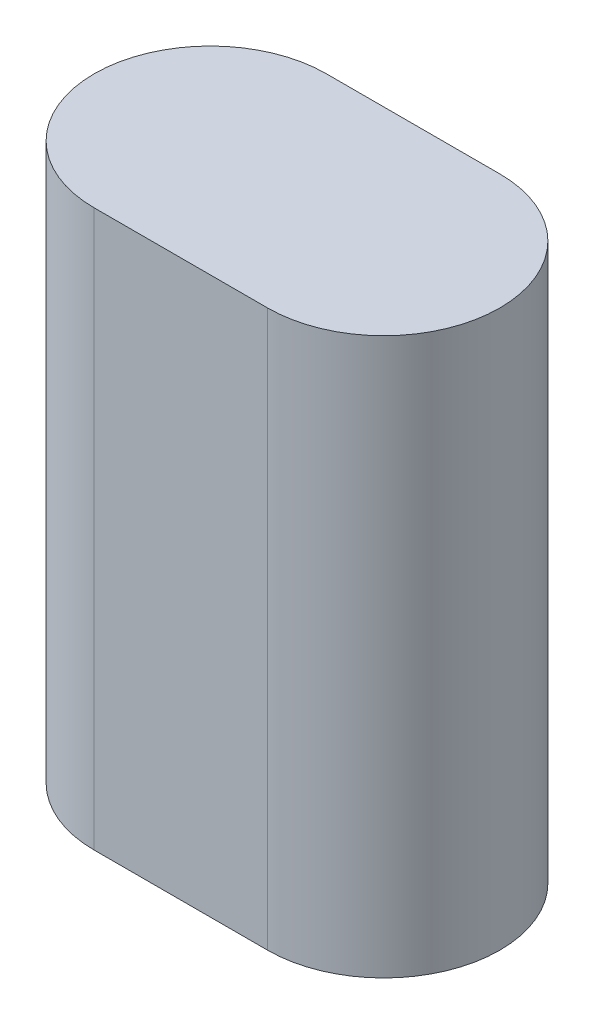
SolidWorks part; units mm, degrees
ref_plane "Front Plane" through (0, 0, 0) normal (0, 0, 1) x (1, 0, 0)
ref_plane "Top Plane" through (0, 0, 0) normal (0, 1, 0) x (1, 0, 0)
ref_plane "Right Plane" through (0, 0, 0) normal (1, 0, 0) x (0, 0, -1)
sketch "Sketch1" plane through (0, 0, 0) normal (0, 1, 0) x (1, 0, 0)
  line L0 (-4.77, 0) -> (4.77, 0) construction
  line L1 (-4.77, 6.385) -> (4.77, 6.385)
  line L2 (-4.77, -6.385) -> (4.77, -6.385)
  line L3 (-11.155, 0) -> (11.155, 0) construction
  arc A0 (-4.77, 6.385) -> (-4.77, -6.385) centre (-4.77, 0) ccw
  arc A1 (4.77, -6.385) -> (4.77, 6.385) centre (4.77, 0) ccw
  point P2 (0, 0)
  dimension "D1" = 12.77
  dimension "D2" = 22.31
extrude "Boss-Extrude1" add sketch "Sketch1" along normal blind 30.59
